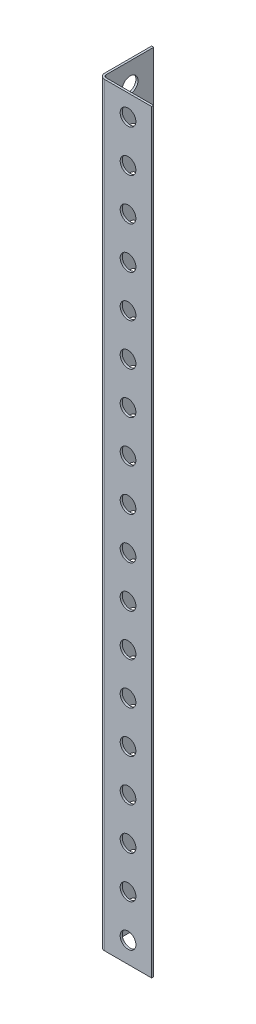
SolidWorks part; units mm, degrees
material "AISI 1020"
ref_plane "Front Plane" through (0, 0, 0) normal (0, 0, 1) x (1, 0, 0)
ref_plane "Top Plane" through (0, 0, 0) normal (0, 1, 0) x (1, 0, 0)
ref_plane "Right Plane" through (0, 0, 0) normal (1, 0, 0) x (0, 0, -1)
sketch "Sketch1" plane through (0, 0, 0) normal (0, 1, 0) x (1, 0, 0)
  line L0 (1.27, 30.48) -> (30.48, 30.48)
  line L1 (0, 0) -> (31.75, 0)
  line L2 (0, 0) -> (0, 31.75)
  line L3 (0, 31.75) -> (31.75, 31.75)
  line L4 (31.75, 0) -> (31.75, 31.75)
  line L5 (30.48, 1.27) -> (30.48, 30.48)
  line L6 (1.27, 1.27) -> (30.48, 1.27)
  line L7 (1.27, 1.27) -> (1.27, 30.48)
  line L8 (1.27, 30.48) -> (1.27, 31.75)
  line L9 (30.48, 1.27) -> (31.75, 1.27)
  dimension "D1" = 31.75
  dimension "D2" = 31.75
  dimension "D3" = 1.27
extrude "Boss-Extrude1" add sketch "Sketch1" along normal blind 1219.2 contours L9 L6 L7 L8 L3 L2 L1 L4
sketch "Sketch3" plane through (0, 0, 0) normal (-1, 0, 0) x (0, 0, 1)
  line L0 (-17.4625, 0) -> (-17.4625, 12.7) construction
  line L2 (-31.75, 1219.2) -> (-31.75, 0) construction
  circle A0 centre (-17.4625, 12.7) radius 4.7625
  circle A1 centre (-17.4625, 38.1) radius 4.7625
  circle A2 centre (-17.4625, 63.5) radius 4.7625
  circle A3 centre (-17.4625, 88.9) radius 4.7625
  circle A4 centre (-17.4625, 114.3) radius 4.7625
  circle A5 centre (-17.4625, 139.7) radius 4.7625
  circle A6 centre (-17.4625, 165.1) radius 4.7625
  circle A7 centre (-17.4625, 190.5) radius 4.7625
  circle A8 centre (-17.4625, 215.9) radius 4.7625
  circle A9 centre (-17.4625, 241.3) radius 4.7625
  circle A10 centre (-17.4625, 266.7) radius 4.7625
  circle A11 centre (-17.4625, 292.1) radius 4.7625
  circle A12 centre (-17.4625, 317.5) radius 4.7625
  circle A13 centre (-17.4625, 342.9) radius 4.7625
  circle A14 centre (-17.4625, 368.3) radius 4.7625
  circle A15 centre (-17.4625, 393.7) radius 4.7625
  circle A16 centre (-17.4625, 419.1) radius 4.7625
  circle A17 centre (-17.4625, 444.5) radius 4.7625
  circle A18 centre (-17.4625, 469.9) radius 4.7625
  circle A19 centre (-17.4625, 495.3) radius 4.7625
  circle A20 centre (-17.4625, 520.7) radius 4.7625
  circle A21 centre (-17.4625, 546.1) radius 4.7625
  circle A22 centre (-17.4625, 571.5) radius 4.7625
  circle A23 centre (-17.4625, 596.9) radius 4.7625
  circle A24 centre (-17.4625, 622.3) radius 4.7625
  circle A25 centre (-17.4625, 647.7) radius 4.7625
  circle A26 centre (-17.4625, 673.1) radius 4.7625
  circle A27 centre (-17.4625, 698.5) radius 4.7625
  circle A28 centre (-17.4625, 723.9) radius 4.7625
  circle A29 centre (-17.4625, 749.3) radius 4.7625
  circle A30 centre (-17.4625, 774.7) radius 4.7625
  circle A31 centre (-17.4625, 800.1) radius 4.7625
  circle A32 centre (-17.4625, 825.5) radius 4.7625
  circle A33 centre (-17.4625, 850.9) radius 4.7625
  circle A34 centre (-17.4625, 876.3) radius 4.7625
  circle A35 centre (-17.4625, 901.7) radius 4.7625
  circle A36 centre (-17.4625, 927.1) radius 4.7625
  circle A37 centre (-17.4625, 952.5) radius 4.7625
  circle A38 centre (-17.4625, 977.9) radius 4.7625
  circle A39 centre (-17.4625, 1003.3) radius 4.7625
  circle A40 centre (-17.4625, 1028.7) radius 4.7625
  circle A41 centre (-17.4625, 1054.1) radius 4.7625
  circle A42 centre (-17.4625, 1079.5) radius 4.7625
  circle A43 centre (-17.4625, 1104.9) radius 4.7625
  circle A44 centre (-17.4625, 1130.3) radius 4.7625
  circle A45 centre (-17.4625, 1155.7) radius 4.7625
  circle A46 centre (-17.4625, 1181.1) radius 4.7625
  circle A47 centre (-17.4625, 1206.5) radius 4.7625
  dimension "D1" = 9.525
  dimension "D2" = 12.7
  dimension "D4" = 14.2875
  dimension "D3" = 48
extrude "Cut-Extrude1" cut sketch "Sketch3" against normal up to next (1.27 mm away)
sketch "Sketch4" plane through (0, 0, 0) normal (0, 0, 1) x (1, 0, 0)
  line L0 (17.4625, 1219.2) -> (17.4625, 1206.5) construction
  line L2 (31.75, 1219.2) -> (31.75, 0) construction
  circle A0 centre (17.4625, 1206.5) radius 4.7625
  circle A1 centre (17.4625, 1181.1) radius 4.7625
  circle A2 centre (17.4625, 1155.7) radius 4.7625
  circle A3 centre (17.4625, 1130.3) radius 4.7625
  circle A4 centre (17.4625, 1104.9) radius 4.7625
  circle A5 centre (17.4625, 1079.5) radius 4.7625
  circle A6 centre (17.4625, 1054.1) radius 4.7625
  circle A7 centre (17.4625, 1028.7) radius 4.7625
  circle A8 centre (17.4625, 1003.3) radius 4.7625
  circle A9 centre (17.4625, 977.9) radius 4.7625
  circle A10 centre (17.4625, 952.5) radius 4.7625
  circle A11 centre (17.4625, 927.1) radius 4.7625
  circle A12 centre (17.4625, 901.7) radius 4.7625
  circle A13 centre (17.4625, 876.3) radius 4.7625
  circle A14 centre (17.4625, 850.9) radius 4.7625
  circle A15 centre (17.4625, 825.5) radius 4.7625
  circle A16 centre (17.4625, 800.1) radius 4.7625
  circle A17 centre (17.4625, 774.7) radius 4.7625
  circle A18 centre (17.4625, 749.3) radius 4.7625
  circle A19 centre (17.4625, 723.9) radius 4.7625
  circle A20 centre (17.4625, 698.5) radius 4.7625
  circle A21 centre (17.4625, 673.1) radius 4.7625
  circle A22 centre (17.4625, 647.7) radius 4.7625
  circle A23 centre (17.4625, 622.3) radius 4.7625
  circle A24 centre (17.4625, 596.9) radius 4.7625
  circle A25 centre (17.4625, 571.5) radius 4.7625
  circle A26 centre (17.4625, 546.1) radius 4.7625
  circle A27 centre (17.4625, 520.7) radius 4.7625
  circle A28 centre (17.4625, 495.3) radius 4.7625
  circle A29 centre (17.4625, 469.9) radius 4.7625
  circle A30 centre (17.4625, 444.5) radius 4.7625
  circle A31 centre (17.4625, 419.1) radius 4.7625
  circle A32 centre (17.4625, 393.7) radius 4.7625
  circle A33 centre (17.4625, 368.3) radius 4.7625
  circle A34 centre (17.4625, 342.9) radius 4.7625
  circle A35 centre (17.4625, 317.5) radius 4.7625
  circle A36 centre (17.4625, 292.1) radius 4.7625
  circle A37 centre (17.4625, 266.7) radius 4.7625
  circle A38 centre (17.4625, 241.3) radius 4.7625
  circle A39 centre (17.4625, 215.9) radius 4.7625
  circle A40 centre (17.4625, 190.5) radius 4.7625
  circle A41 centre (17.4625, 165.1) radius 4.7625
  circle A42 centre (17.4625, 139.7) radius 4.7625
  circle A43 centre (17.4625, 114.3) radius 4.7625
  circle A44 centre (17.4625, 88.9) radius 4.7625
  circle A45 centre (17.4625, 63.5) radius 4.7625
  circle A46 centre (17.4625, 38.1) radius 4.7625
  circle A47 centre (17.4625, 12.7) radius 4.7625
  dimension "D1" = 9.525
  dimension "D2" = 12.7
  dimension "D4" = 14.2875
  dimension "D3" = 48
extrude "Cut-Extrude2" cut sketch "Sketch4" against normal up to next (1.27 mm away)
fillet "Fillet1" radius 3.175 1 edges at (0, 609.6, 0)
fillet "Fillet2" radius 1.5875 1 edges at (1.27, 609.6, -1.27)
sketch "Sketch5" plane through (0, 1219.2, 0) normal (0, 1, 0) x (1, 0, 0)
  line L12 (0, 31.75) -> (0, 3.175)
  line L13 (3.175, 0) -> (31.75, 0)
  line L14 (31.75, 0) -> (31.75, 1.27)
  line L15 (31.75, 1.27) -> (2.8575, 1.27)
  line L16 (1.27, 2.8575) -> (1.27, 31.75)
  line L17 (1.27, 31.75) -> (0, 31.75)
  line L18 (0, 31.75) -> (0, 3.175)
  line L19 (3.175, 0) -> (31.75, 0)
  line L20 (31.75, 0) -> (31.75, 1.27)
  line L21 (31.75, 1.27) -> (2.8575, 1.27)
  line L22 (1.27, 2.8575) -> (1.27, 31.75)
  line L23 (1.27, 31.75) -> (0, 31.75)
  arc A4 (0, 3.175) -> (3.175, 0) centre (3.175, 3.175) ccw
  arc A5 (1.27, 2.8575) -> (2.8575, 1.27) centre (2.8575, 2.8575) ccw
  arc A6 (0, 3.175) -> (3.175, 0) centre (3.175, 3.175) ccw
  arc A7 (1.27, 2.8575) -> (2.8575, 1.27) centre (2.8575, 2.8575) ccw
  dimension "D1" = 0
extrude "Cut-Extrude3" cut sketch "Sketch5" against normal blind 762
